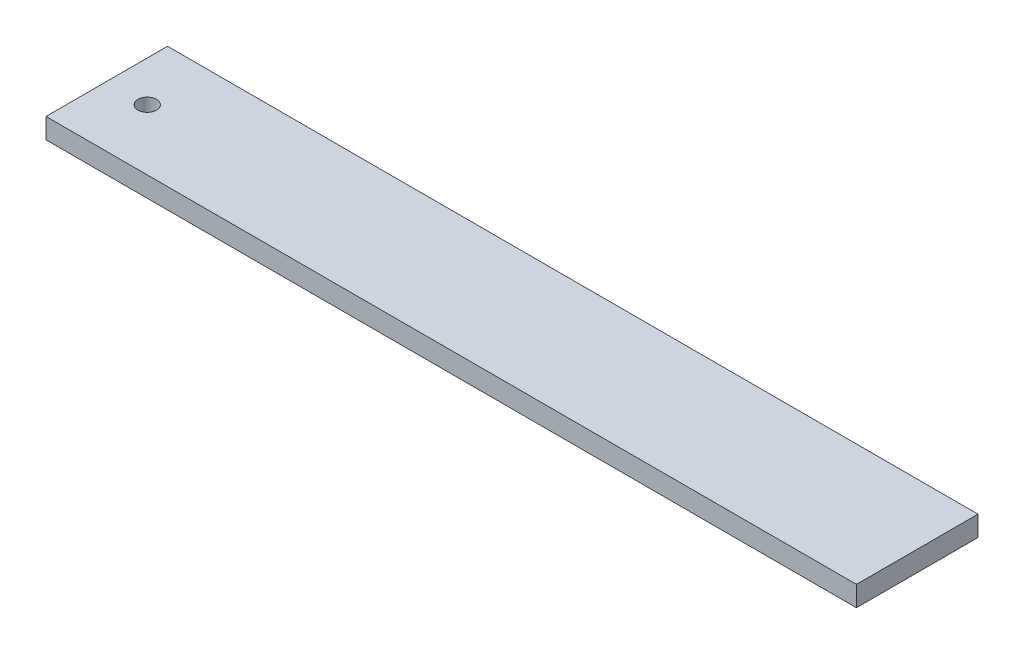
SolidWorks part; units mm, degrees
ref_plane "Front Plane" through (0, 0, 0) normal (0, 0, 1) x (1, 0, 0)
ref_plane "Top Plane" through (0, 0, 0) normal (0, 1, 0) x (1, 0, 0)
ref_plane "Right Plane" through (0, 0, 0) normal (1, 0, 0) x (0, 0, -1)
sketch "Sketch1" plane through (0, 0, 0) normal (0, 1, 0) x (1, 0, 0)
  line L1 (0, 0) -> (127, 0)
  line L2 (0, 0) -> (0, 19.05)
  line L3 (0, 19.05) -> (127, 19.05)
  line L4 (127, 0) -> (127, 19.05)
  circle A0 centre (6.35, 9.525) radius 1.4605
  dimension "D3" = 2.921
  dimension "D1" = 19.05
  dimension "D2" = 127
  dimension "D4" = 6.35
  dimension "D5" = 9.525
extrude "Boss-Extrude1" add sketch "Sketch1" along normal blind 3.175
